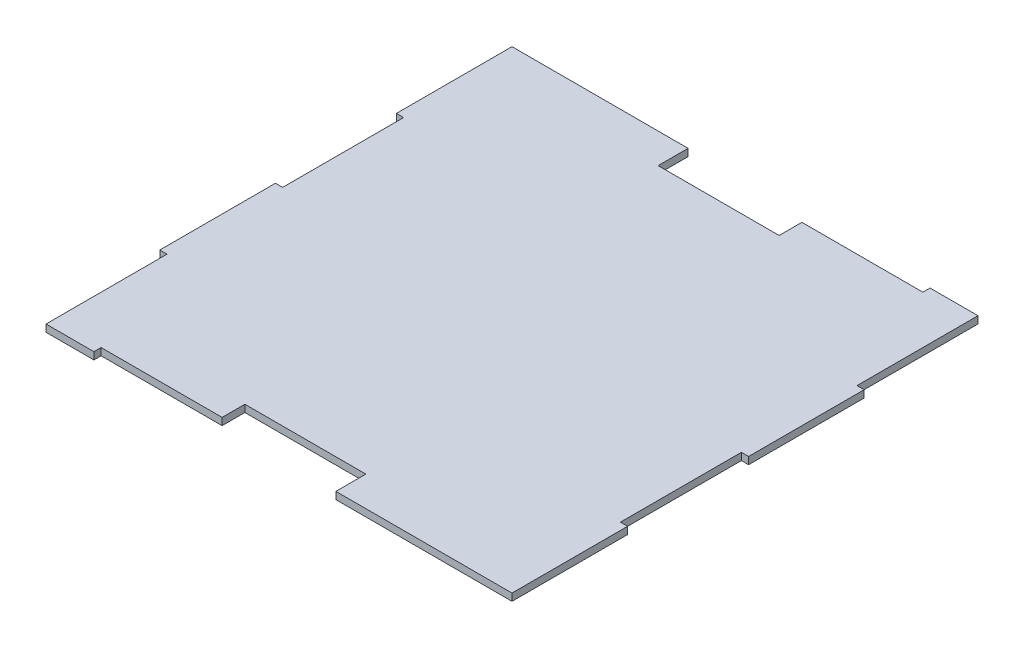
SolidWorks part; units mm, degrees
ref_plane "Front Plane" through (0, 0, 0) normal (0, 0, 1) x (1, 0, 0)
ref_plane "Top Plane" through (0, 0, 0) normal (0, 1, 0) x (1, 0, 0)
ref_plane "Right Plane" through (0, 0, 0) normal (1, 0, 0) x (0, 0, -1)
sketch "Sketch1" plane through (0, 0, 0) normal (0, 1, 0) x (1, 0, 0)
  line L1 (-197.5, -197.5) -> (197.5, -197.5)
  line L2 (-197.5, -197.5) -> (-197.5, 197.5)
  line L3 (-197.5, 197.5) -> (197.5, 197.5)
  line L4 (197.5, -197.5) -> (197.5, 197.5)
  line L5 (-197.5, -197.5) -> (197.5, 197.5) construction
  line L6 (-197.5, 197.5) -> (197.5, -197.5) construction
  line L7 (-50.5, 222.5) -> (50.5, 222.5)
  line L8 (-50.5, 222.5) -> (-50.5, 172.5)
  line L9 (-50.5, 172.5) -> (50.5, 172.5)
  line L10 (50.5, 222.5) -> (50.5, 172.5)
  line L11 (-50.5, 222.5) -> (50.5, 172.5) construction
  line L12 (-50.5, 172.5) -> (50.5, 222.5) construction
  line L13 (-50.5, -222.5) -> (50.5, -222.5)
  line L14 (-50.5, -222.5) -> (-50.5, -172.5)
  line L15 (-50.5, -172.5) -> (50.5, -172.5)
  line L16 (50.5, -222.5) -> (50.5, -172.5)
  line L17 (-50.5, -222.5) -> (50.5, -172.5) construction
  line L18 (-50.5, -172.5) -> (50.5, -222.5) construction
  line L43 (50.5, 197.5) -> (151.5, 197.5)
  line L44 (50.5, 197.5) -> (50.5, 191.5)
  line L45 (50.5, 191.5) -> (151.5, 191.5)
  line L46 (151.5, 197.5) -> (151.5, 191.5)
  line L47 (-50.5, -197.5) -> (-151.5, -197.5)
  line L48 (-50.5, -197.5) -> (-50.5, -191.5)
  line L49 (-50.5, -191.5) -> (-151.5, -191.5)
  line L50 (-151.5, -197.5) -> (-151.5, -191.5)
  line L51 (-197.5, -197.5) -> (-191.5, -197.5)
  line L52 (-197.5, -197.5) -> (-197.5, -96.5)
  line L53 (-197.5, -96.5) -> (-191.5, -96.5)
  line L54 (-191.5, -197.5) -> (-191.5, -96.5)
  line L55 (-197.5, 0) -> (-191.5, 0)
  line L56 (-197.5, 0) -> (-197.5, 101)
  line L57 (-197.5, 101) -> (-191.5, 101)
  line L58 (-191.5, 0) -> (-191.5, 101)
  line L59 (197.5, 197.5) -> (191.5, 197.5)
  line L60 (197.5, 197.5) -> (197.5, 96.5)
  line L61 (197.5, 96.5) -> (191.5, 96.5)
  line L62 (191.5, 197.5) -> (191.5, 96.5)
  line L63 (197.5, 0) -> (191.5, 0)
  line L64 (197.5, 0) -> (197.5, -101)
  line L65 (197.5, -101) -> (191.5, -101)
  line L66 (191.5, 0) -> (191.5, -101)
  point P0 (0, 0)
  point P6 (0, 197.5)
  point P11 (0, -197.5)
  dimension "D1" = 395
  dimension "D2" = 101
  dimension "D3" = 50
  dimension "D4" = 101
  dimension "D5" = 6
extrude "Boss-Extrude1" add sketch "Sketch1" along normal blind 6
